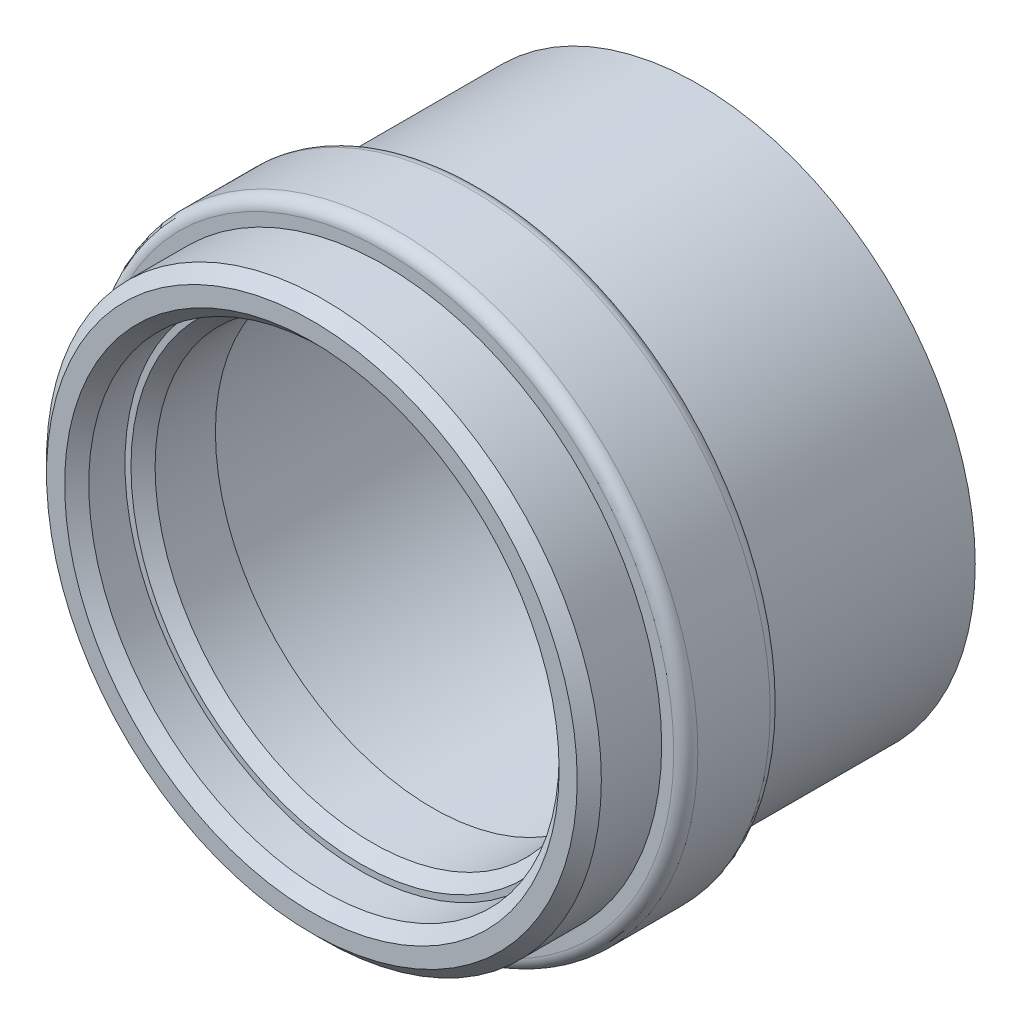
SolidWorks part; units mm, degrees
ref_plane "前视基准面" through (0, 0, 0) normal (0, 0, 1) x (1, 0, 0)
ref_plane "上视基准面" through (0, 0, 0) normal (0, 1, 0) x (1, 0, 0)
ref_plane "右视基准面" through (0, 0, 0) normal (1, 0, 0) x (0, 0, -1)
sketch "草图1" plane through (0, 0, 0) normal (0, 0, 1) x (1, 0, 0)
  circle A0 centre (0, 0) radius 11.5
  dimension "D1" = 23
extrude "凸台-拉伸1" add sketch "草图1" along normal blind 16
sketch "草图2" plane through (0, 0, 16) normal (0, 0, 1) x (1, 0, 0)
  circle A0 centre (0, 0) radius 12.5
  dimension "D1" = 25
extrude "凸台-拉伸2" add sketch "草图2" against normal blind 4 from offset 3 offset against normal yes
sketch "草图3" plane through (0, 0, 16) normal (0, 0, 1) x (1, 0, 0)
  circle A0 centre (0, 0) radius 9.75
  dimension "D1" = 19.5
extrude "切除-拉伸1" cut sketch "草图3" against normal blind 2
sketch "草图4" plane through (0, 0, 14) normal (0, 0, 1) x (1, 0, 0)
  circle A0 centre (0, 0) radius 9
  dimension "D1" = 18
extrude "切除-拉伸2" cut sketch "草图4" against normal through all
sketch "草图5" plane through (0, 0, 0) normal (0, 0, -1) x (-1, 0, 0)
  circle A0 centre (0, 0) radius 10
  dimension "D1" = 20
extrude "切除-拉伸3" cut sketch "草图5" against normal blind 11
chamfer "倒角1" distance 0.5 angle 45 4 edges at (9, 0, 14) (9.75, 0, 16) (-10, 0, 0) (11.5, 0, 16)
fillet "圆角1" radius 0.5 2 edges at (12.5, 0, 9) (12.5, 0, 13)
